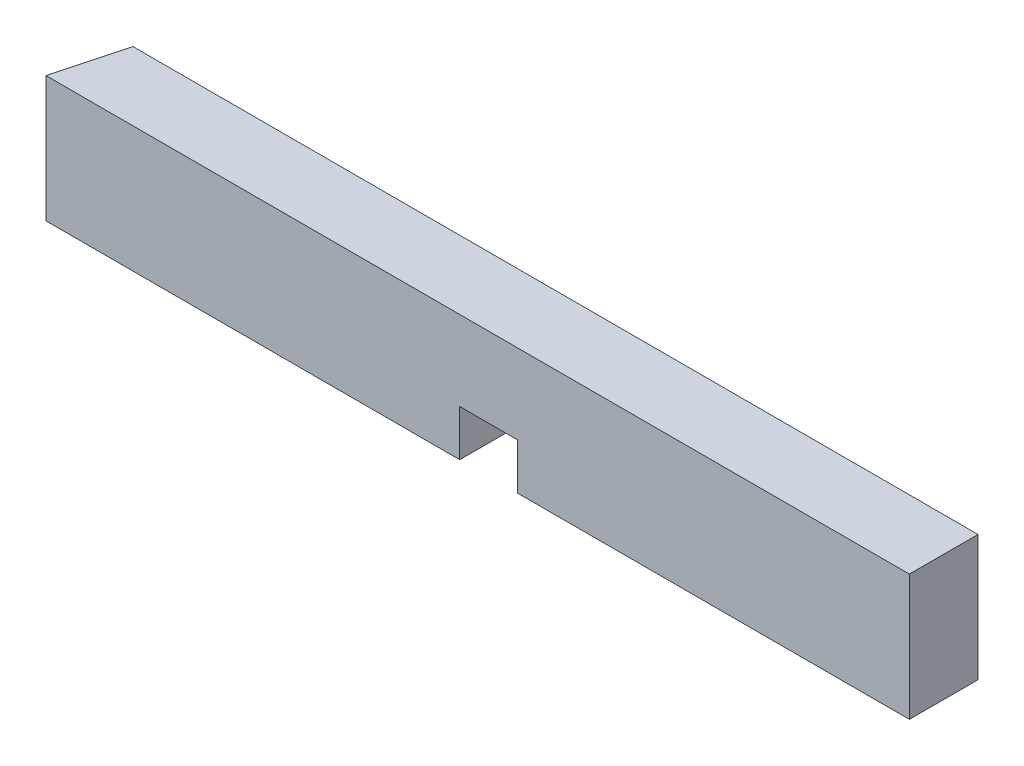
SolidWorks part; units mm, degrees
material "AISI 1020"
ref_plane "Alzado" through (0, 0, 0) normal (0, 0, 1) x (1, 0, 0)
ref_plane "Planta" through (0, 0, 0) normal (0, 1, 0) x (1, 0, 0)
ref_plane "Vista lateral" through (0, 0, 0) normal (1, 0, 0) x (0, 0, -1)
sketch "Croquis1" plane through (0, 0, 0) normal (0, 0, 1) x (1, 0, 0)
  line L1 (0, 0) -> (58.7375, 0)
  line L2 (0, 0) -> (0, 8.6614)
  line L3 (0, 8.6614) -> (58.7375, 8.6614)
  line L4 (58.7375, 0) -> (58.7375, 8.6614)
  dimension "D1" = 58.7375
  dimension "D2" = 8.6614
extrude "Saliente-Extruir1" add sketch "Croquis1" along normal blind 4.7244
sketch "Croquis2" plane through (0, 0, 0) normal (0, 0, 1) x (1, 0, 0)
  line L0 (0, 0) -> (58.7375, 0) construction
  line L1 (27.7812, 0) -> (31.75, 0)
  line L2 (27.7812, 0) -> (27.7812, 3.175)
  line L3 (27.7812, 3.175) -> (31.75, 3.175)
  line L4 (31.75, 0) -> (31.75, 3.175)
  line L5 (0, 8.6614) -> (0, 0) construction
  dimension "D1" = 3.9688
  dimension "D2" = 3.175
  dimension "D3" = 27.7812
extrude "Cortar-Extruir2" cut sketch "Croquis2" against normal through all and the other way through all
sketch "Croquis4" plane through (0, 8.6614, 0) normal (0, 1, 0) x (1, 0, 0)
  line L0 (58.7375, 0) -> (0.5715, 0) construction
  line L1 (58.7375, 0) -> (0, 0) construction
  line L3 (0, -2.5012) -> (0.5715, 0)
  line L5 (0, -2.5012) -> (0, 0)
  line L11 (0.5715, 0) -> (0, 0)
  dimension "D1" = 58.166
extrude "Cortar-Extruir4" cut sketch "Croquis4" against normal through all
sketch "Croquis5" plane through (0, 8.6614, 0) normal (0, 1, 0) x (1, 0, 0)
  line L0 (58.7375, -4.7244) -> (-0.6985, -4.7244) construction
  line L1 (0.5715, 0) -> (-0.6985, -4.7244)
  line L2 (-0.6985, -4.7244) -> (0.2857, -4.7244)
  line L3 (0.2857, -4.7244) -> (0.5715, 0)
  dimension "D1" = 59.436
extrude "Saliente-Extruir2" add sketch "Croquis5" against normal up to vertex (8.6614 mm away)
